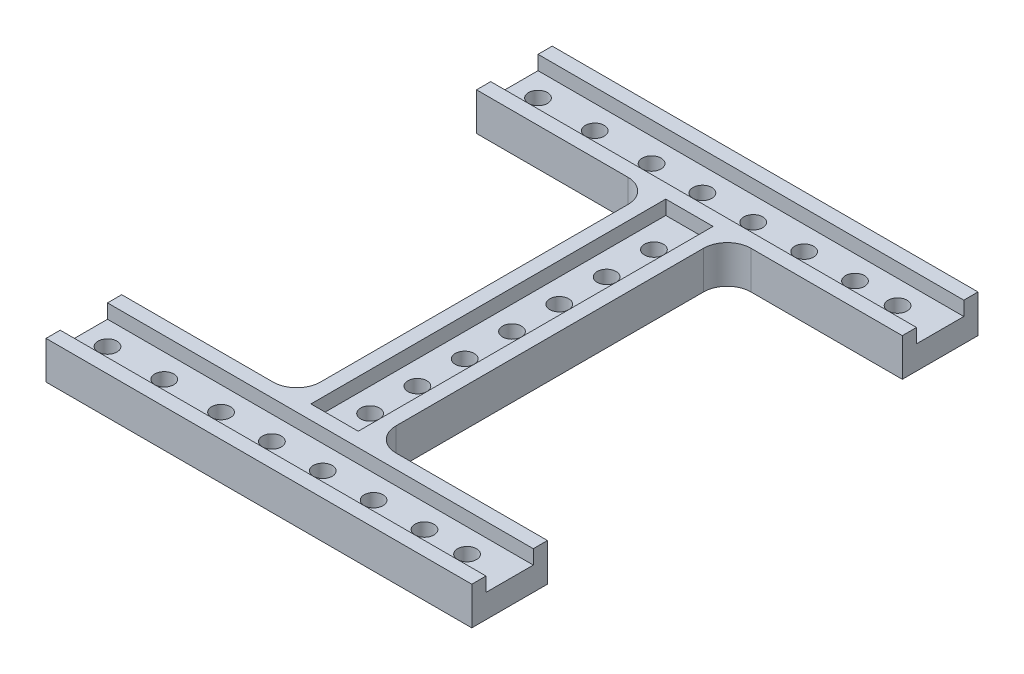
SolidWorks part; units mm, degrees
ref_plane "Front Plane" through (0, 0, 0) normal (0, 0, 1) x (1, 0, 0)
ref_plane "Top Plane" through (0, 0, 0) normal (0, 1, 0) x (1, 0, 0)
ref_plane "Right Plane" through (0, 0, 0) normal (1, 0, 0) x (0, 0, -1)
sketch "Sketch1" plane through (0, 0, 0) normal (0, 1, 0) x (1, 0, 0)
  line L1 (-51.7944, 9.8071) -> (38.2056, 9.8071)
  line L2 (-51.7944, 9.8071) -> (-51.7944, -6.1929)
  line L3 (-51.7944, -6.1929) -> (38.2056, -6.1929)
  line L4 (38.2056, 9.8071) -> (38.2056, -6.1929)
extrude "Boss-Extrude1" add sketch "Sketch1" along normal blind 5
sketch "Sketch2" plane through (0, 5, 0) normal (0, 1, 0) x (1, 0, 0)
  line L0 (-51.7944, 9.8071) -> (-51.7944, 6.8071)
  line L1 (-51.7944, 9.8071) -> (-51.7944, -6.1929) construction
  line L2 (-51.7944, 6.8071) -> (38.2056, 6.8071)
  line L3 (38.2056, -6.1929) -> (38.2056, 9.8071) construction
  line L4 (38.2056, 6.8071) -> (38.2056, 9.8071)
  line L5 (38.2056, 9.8071) -> (-51.7944, 9.8071)
  line L6 (-51.7944, -6.1929) -> (-51.7944, -3.1929)
  line L7 (-51.7944, -3.1929) -> (38.2056, -3.1929)
  line L8 (38.2056, -3.1929) -> (38.2056, -6.1929)
  line L9 (38.2056, -6.1929) -> (-51.7944, -6.1929)
extrude "Boss-Extrude2" add sketch "Sketch2" along normal blind 3
sketch "Sketch3" plane through (0, 0, 0) normal (0, -1, 0) x (1, 0, 0)
  circle A0 centre (20.2056, -1.8071) radius 2
  circle A1 centre (-22.7944, -1.8071) radius 2
extrude "Cut-Extrude2" cut sketch "Sketch3" against normal up to surface (5 mm away) up to face at (-6.7944, 5, -1.8071)
sketch "Sketch4" plane through (0, 0, 0) normal (0, -1, 0) x (1, 0, 0)
  line L0 (20.2056, -1.8071) -> (20.2056, -92.8071)
  line L1 (38.2056, -84.8071) -> (38.2056, -100.8071)
  line L2 (38.2056, -100.8071) -> (-51.7944, -100.8071)
  line L3 (-51.7944, -100.8071) -> (-51.7944, -84.8071)
  line L4 (-51.7944, -84.8071) -> (38.2056, -84.8071)
  circle A0 centre (20.2056, -92.8071) radius 2
  circle A1 centre (-22.7944, -92.8071) radius 2
extrude "Boss-Extrude3" add sketch "Sketch4" against normal blind 5 separate body
sketch "Sketch5" plane through (0, 5, 0) normal (0, 1, 0) x (1, 0, 0)
  line L0 (38.2056, 100.8071) -> (38.2056, 97.8071)
  line L1 (38.2056, 84.8071) -> (38.2056, 100.8071) construction
  line L2 (38.2056, 97.8071) -> (-51.7944, 97.8071)
  line L3 (-51.7944, 100.8071) -> (-51.7944, 84.8071) construction
  line L4 (-51.7944, 97.8071) -> (-51.7944, 100.8071)
  line L5 (-51.7944, 100.8071) -> (38.2056, 100.8071)
  line L6 (38.2056, 84.8071) -> (38.2056, 87.8071)
  line L7 (38.2056, 87.8071) -> (-51.7944, 87.8071)
  line L8 (-51.7944, 87.8071) -> (-51.7944, 84.8071)
  line L9 (-51.7944, 84.8071) -> (38.2056, 84.8071)
extrude "Boss-Extrude4" add sketch "Sketch5" along normal blind 3
sketch "Sketch6" plane through (0, 0, 0) normal (0, -1, 0) x (1, 0, 0)
  line L1 (38.2056, -9.8071) -> (-51.7944, -9.8071) construction
  line L2 (-51.7944, -84.8071) -> (38.2056, -84.8071) construction
  line L3 (-6.7944, -84.8071) -> (1.2056, -84.8071)
  line L4 (1.2056, -84.8071) -> (1.2056, -9.8071)
  line L5 (1.2056, -9.8071) -> (-14.7944, -9.8071)
  line L6 (-14.7944, -9.8071) -> (-14.7944, -84.8071)
  line L7 (-14.7944, -84.8071) -> (-6.7944, -84.8071)
extrude "Boss-Extrude5" add sketch "Sketch6" against normal blind 5 contours L3 L4 L5 L6 L7
sketch "Sketch7" plane through (0, 5, 0) normal (0, 1, 0) x (1, 0, 0)
  line L0 (1.2056, 84.8071) -> (-1.7944, 84.8071)
  line L1 (-14.7944, 84.8071) -> (1.2056, 84.8071) construction
  line L2 (-1.7944, 84.8071) -> (-1.7944, 9.8071)
  line L3 (1.2056, 9.8071) -> (-14.7944, 9.8071) construction
  line L4 (-1.7944, 9.8071) -> (1.2056, 9.8071)
  line L5 (1.2056, 9.8071) -> (1.2056, 84.8071)
  line L6 (-14.7944, 9.8071) -> (-11.7944, 9.8071)
  line L7 (-11.7944, 9.8071) -> (-11.7944, 84.8071)
  line L8 (-11.7944, 84.8071) -> (-14.7944, 84.8071)
  line L10 (-14.7944, 84.8071) -> (-14.7944, 9.8071)
extrude "Boss-Extrude6" add sketch "Sketch7" along normal blind 3
sketch "Sketch8" plane through (0, 5, 0) normal (0, 1, 0) x (1, 0, 0)
  circle A0 centre (-46.7944, 92.8071) radius 2
  circle A2 centre (-34.7944, 92.8071) radius 2
  circle A3 centre (29.2056, 92.8071) radius 2
  circle A4 centre (9.4556, 92.8071) radius 2
  circle A5 centre (-1.2944, 92.8071) radius 2
  circle A7 centre (-12.0444, 92.8071) radius 2
  circle A8 centre (-1.2944, 1.8071) radius 2
  circle A9 centre (-12.0444, 1.8071) radius 2
  circle A10 centre (9.4556, 1.8071) radius 2
  circle A11 centre (-34.7944, 1.8071) radius 2
  circle A12 centre (29.2056, 1.8071) radius 2
  circle A13 centre (-46.7944, 1.8071) radius 2
extrude "Cut-Extrude5" cut sketch "Sketch8" against normal up to surface (5 mm away) up to face at (20.2056, 0, -3.8071)
sketch "Sketch9" plane through (0, 5, 0) normal (0, 1, 0) x (1, 0, 0)
  circle A0 centre (-6.7944, 47.3071) radius 2
  circle A1 centre (-6.7944, 57.3071) radius 2
  circle A2 centre (-6.7944, 67.3071) radius 2
  circle A3 centre (-6.7944, 77.3071) radius 2
  circle A4 centre (-6.7944, 37.3071) radius 2
  circle A5 centre (-6.7944, 27.3071) radius 2
  circle A6 centre (-6.7944, 17.3071) radius 2
  dimension "D1" = 4
  dimension "D2" = 4
extrude "Cut-Extrude6" cut sketch "Sketch9" against normal up to surface (5 mm away) up to face at (-34.7944, 0, 0.1929)
fillet "Fillet1" radius 5 4 edges at (-14.7944, 4, -84.8071) (-14.7944, 4, -9.8071) (1.2056, 4, -9.8071) (1.2056, 4, -84.8071)
sketch "Sketch10" plane through (0, 0, 0) normal (0, -1, 0) x (1, 0, 0)
  circle A0 centre (20.2056, -1.8071) radius 4
  circle A1 centre (-22.7944, -1.8071) radius 4
  circle A2 centre (20.2056, -92.8071) radius 4
  circle A3 centre (-22.7944, -92.8071) radius 4
extrude "Cut-Extrude7" cut sketch "Sketch10" against normal blind 2
sketch "Sketch11" plane through (0, 0, 0) normal (0, -1, 0) x (1, 0, 0)
  circle A0 centre (-46.7944, -1.8071) radius 4
  circle A1 centre (-46.7944, -92.8071) radius 4
extrude "Cut-Extrude8" cut sketch "Sketch11" against normal blind 2
